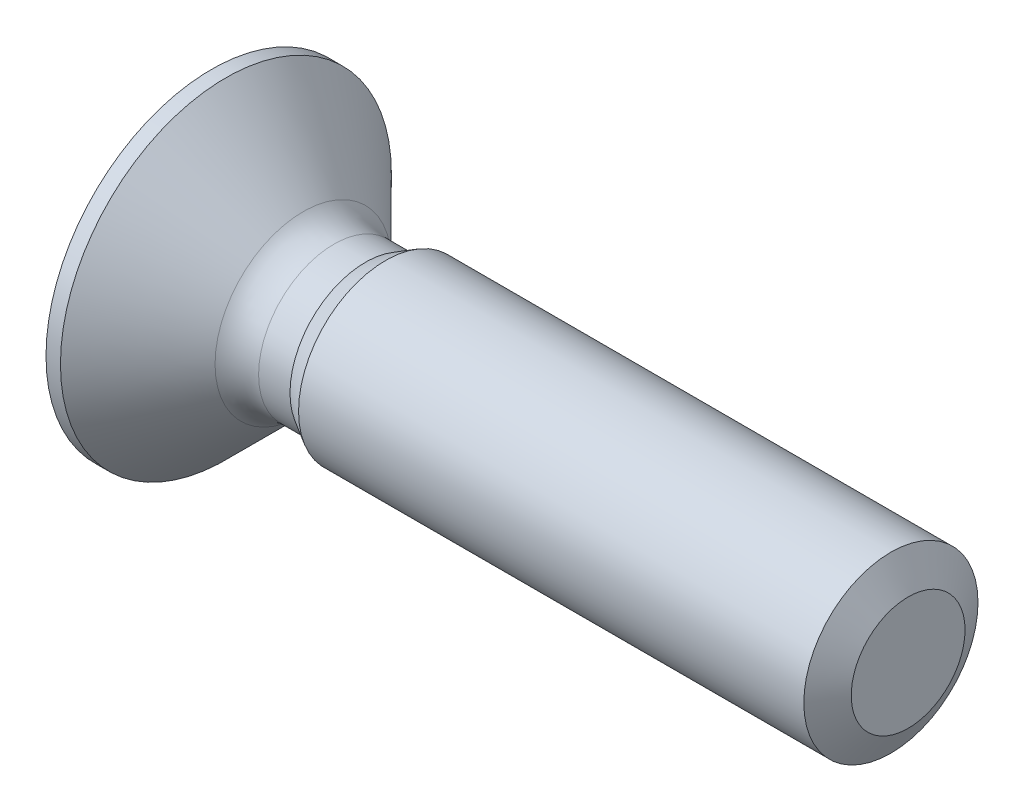
SolidWorks part; units mm, degrees
revolve "基体-旋转" add sketch "草图1" angle 360 about L0
sketch "草图1" plane through (0, 0, 0) normal (0, 0, 1) x (1, 0, 0)
  line L0 (0, 0) -> (4.4175, 0) construction
  line L1 (0, 0) -> (0, 1.9)
  line L2 (0, 1.9) -> (0.166, 1.9)
  line L3 (0.166, 1.9) -> (1.0536, 1.0124)
  line L4 (1.4071, 0.866) -> (1.7679, 0.866)
  line L5 (1.7679, 0.866) -> (2, 1)
  line L6 (2, 1) -> (8, 1)
  line L7 (8, 1) -> (8, 0)
  line L8 (0, 0) -> (8, 0)
  arc A0 (1.4071, 0.866) -> (1.0536, 1.0124) centre (1.4071, 1.366) cw
  point P12 (1.2, 0.866)
  dimension "D2" = 0.5
  dimension "D1" = 1.732
  dimension "d" = 2
  dimension "dk" = 3.8
  dimension "k" = 1.2
  dimension "D5" = 45
  dimension "a" = 0.8
  dimension "l" = 8
  dimension "D8" = 30
cosmetic thread "装饰螺纹线2" parameters "D1"=6, "D2"=1.6
material "AISI 304"
ref_plane "前视" through (0, 0, 0) normal (0, 0, 1) x (1, 0, 0)
ref_plane "上视" through (0, 0, 0) normal (0, 1, 0) x (1, 0, 0)
ref_plane "右视" through (0, 0, 0) normal (1, 0, 0) x (0, 0, -1)
sketch "尺寸草图" plane through (0, 0, 0) normal (0, 0, 1) x (1, 0, 0)
  line L0 (0, 0) -> (8, 0)
  point P3 (1.2, 0)
  point P4 (0.8, 0)
  point P5 (2, 0)
  point P6 (3.8, 0)
  point P7 (6.1, 0)
  point P8 (3.5943, 0)
  point P9 (7.5, 0)
  point P10 (6.8, 0)
  point P11 (7.6, 0)
  dimension "d" = 2
  dimension "dk" = 3.8
  dimension "k" = 1.2
  dimension "a" = 0.8
  dimension "l" = 8
  dimension "r" = 0.5
  dimension "m" = 1.9
  dimension "h" = 1.2
  dimension "p" = 0.4
sketch "草图2" plane through (0, 0, 0) normal (0, 0, 1) x (1, 0, 0)
  line L0 (7.8022, 1) -> (8.2022, 1)
  line L1 (8.2022, 1) -> (8, 0.6536)
  line L2 (8, 0.6536) -> (7.8022, 1)
  line L3 (8, -1) -> (8, 1) construction
  line L6 (0, 0) -> (-0.4315, 0) construction
  dimension "D1" = 0.4
  dimension "D2" = 0.3464
  dimension "D3" = 1
  dimension "D4" = 60
revolve "切除-旋转1" cut sketch "草图2" angle 360 about L6
pattern_linear "阵列(线性)1" [suppressed] count 15 spacing 0.4 along (1, 0, 0)
sketch "草图3" plane through (0, 0, 0) normal (-1, 0, 0) x (0, 0, 1)
  line L0 (0, 0) -> (1.6329, 0) construction
  line L1 (0, 0) -> (0, 0.8499) construction
  line L2 (-0.95, 0.2) -> (0.95, 0.2)
  line L3 (-0.95, 0.2) -> (-0.95, -0.2)
  line L4 (-0.95, -0.2) -> (0.95, -0.2)
  line L5 (0.95, 0.2) -> (0.95, -0.2)
  dimension "m" = 1.9
  dimension "D1" = 0.4
ref_plane "基准面1" through (1.2, 0, 0) normal (-1, 0, 0) x (0, 0, 1)
sketch "草图4" plane through (1.2, 0, 0) normal (-1, 0, 0) x (0, 0, 1)
  point P0 (0, 0)
loft "切除-放样1" cut profiles "草图3", "草图4"
pattern_circular "阵列(圆周)1" count 2 every 90 about axis through (0, 0, 0) along (1, 0, 0) of "切除-放样1"
equation "\"l@草图1\" = \"l@尺寸草图\""
equation "\"k@草图1\" = \"k@尺寸草图\""
equation "\"a@草图1\" = \"a@尺寸草图\""
equation "\"d@草图1\" = \"d@尺寸草图\""
equation "\"dk@草图1\" = \"dk@尺寸草图\""
equation "\"D2@草图1\" = \"r@尺寸草图\""
equation "\"m@草图3\" = \"m@尺寸草图\""
equation "\"h@基准面1\" = \"h@尺寸草图\""
equation "\"D3@阵列(线性)1\" = \"p@尺寸草图\""
equation "\"D3@草图2\" = \"d@草图1\" / 2"
equation "\"D1@装饰螺纹线2\" = \"l@草图1\" - \"k@草图1\" - \"a@草图1\""
equation "\"D2@装饰螺纹线2\" = \"d@尺寸草图\"- \"p@尺寸草图\""
equation "\"D1@阵列(线性)1\" = (  \"l@草图1\" - \"k@草图1\" - \"a@草图1\" )  / \"p@尺寸草图\""
equation "\"D1@草图3\" = \"p@尺寸草图\""
equation "\"D1@草图1\" = \"d@尺寸草图\"*0.866"
equation "\"D2@草图2\" = \"p@尺寸草图\"*0.866"
equation "\"D1@草图2\" = \"p@尺寸草图\""
